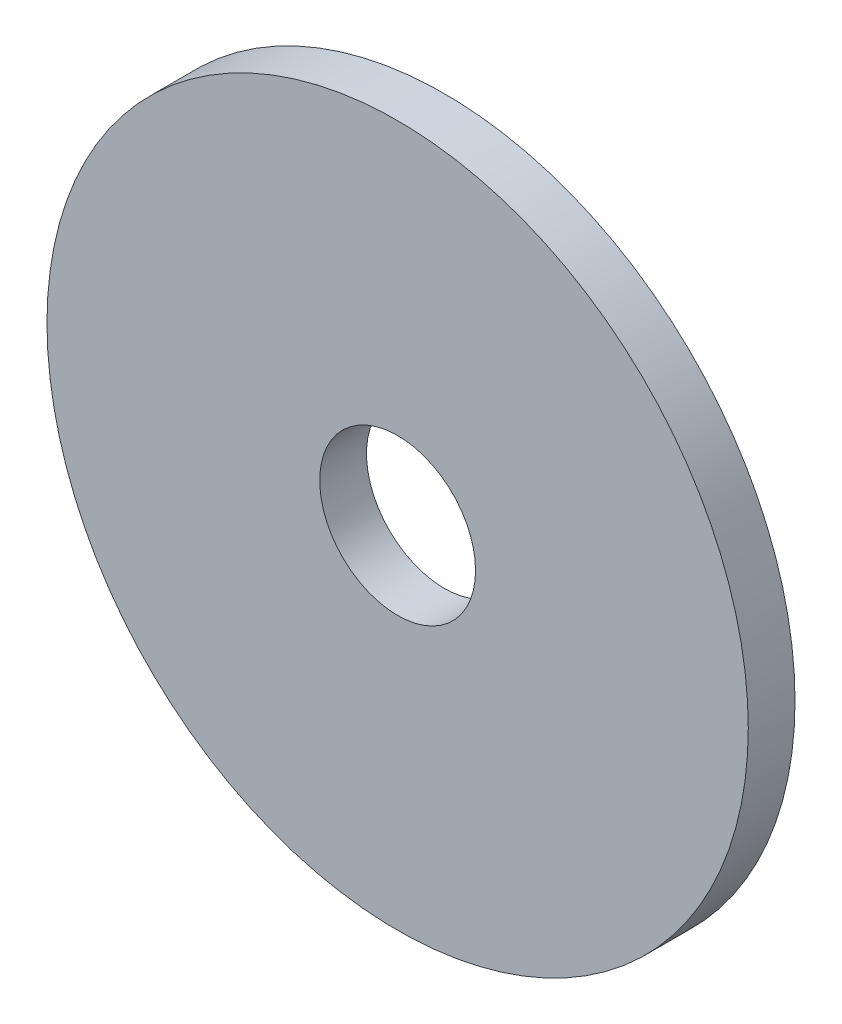
SolidWorks part; units mm, degrees
ref_plane "Front Plane" through (0, 0, 0) normal (0, 0, 1) x (1, 0, 0)
ref_plane "Top Plane" through (0, 0, 0) normal (0, 1, 0) x (1, 0, 0)
ref_plane "Right Plane" through (0, 0, 0) normal (1, 0, 0) x (0, 0, -1)
sketch "Sketch1" plane through (0, 0, 0) normal (0, 0, 1) x (1, 0, 0)
  circle A0 centre (0, 0) radius 22.5
  circle A1 centre (0, 0) radius 5
  dimension "D1" = 45
  dimension "D2" = 10
extrude "Boss-Extrude1" add sketch "Sketch1" along normal blind 3
